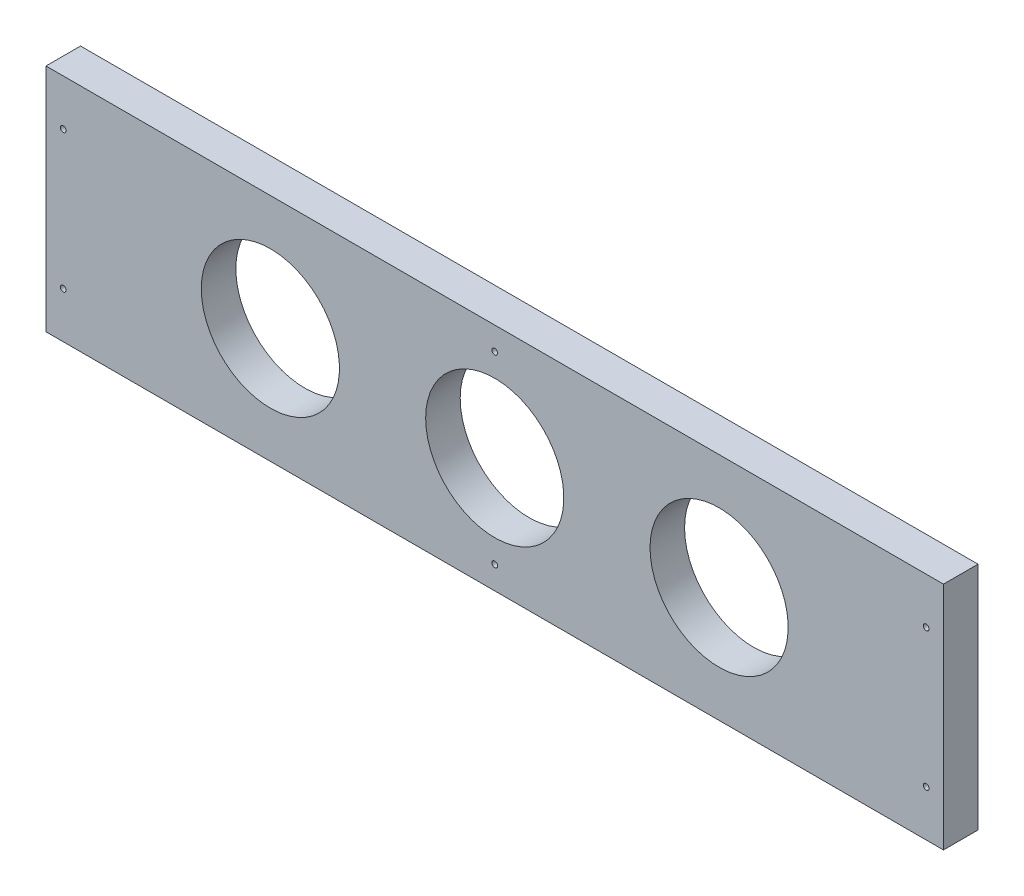
SolidWorks part; units mm, degrees
material "Beech"
ref_plane "Front Plane" through (0, 0, 0) normal (0, 0, 1) x (1, 0, 0)
ref_plane "Top Plane" through (0, 0, 0) normal (0, 1, 0) x (1, 0, 0)
ref_plane "Right Plane" through (0, 0, 0) normal (1, 0, 0) x (0, 0, -1)
sketch "Sketch1" plane through (0, 0, 0) normal (0, 0, 1) x (1, 0, 0)
  line L0 (-157.3266, 4967.6971) -> (-157.3266, 5284.8315) construction
  line L5 (-157.3266, 5411.8315) -> (337.7194, 5411.8315)
  line L6 (-157.3266, 5411.8315) -> (-157.3266, 5284.8315)
  line L7 (-157.3266, 5284.8315) -> (337.7194, 5284.8315)
  line L9 (90.1964, 5267.1362) -> (90.1964, 5460.8032) construction
  line L10 (26.6964, 5267.1362) -> (153.6964, 5267.1362) construction
  line L11 (-176.3766, 5460.8032) -> (356.7694, 5460.8032) construction
  line L12 (-157.3266, 5348.3315) -> (90.1964, 5348.3315) construction
  line L13 (337.7194, 5411.8315) -> (337.7194, 5284.8315)
  point P12 (-76.4911, 5348.3315)
  point P17 (90.1964, 5411.8315)
  point P18 (90.1964, 5284.8315)
  dimension "D1" = 127
extrude "Boss-Extrude1" add sketch "Sketch1" along normal blind 19.05
sketch "Sketch2" plane through (0, 0, 0) normal (0, 0, -1) x (-1, 0, 0)
  line L0 (-337.7194, 5348.3315) -> (-90.1964, 5348.3315) construction
  line L1 (-337.7194, 5284.8315) -> (-337.7194, 5411.8315) construction
  line L3 (-90.1964, 5411.8315) -> (-90.1964, 5284.8315) construction
  line L4 (-337.7194, 5411.8315) -> (157.3266, 5411.8315) construction
  line L5 (157.3266, 5284.8315) -> (-337.7194, 5284.8315) construction
  circle A0 centre (-213.9579, 5348.3315) radius 38.1
  circle A1 centre (-90.1964, 5348.3315) radius 38.1
  circle A2 centre (33.5651, 5348.3315) radius 38.1
  dimension "D1" = 76.2
  dimension "D2" = 123.7615
extrude "Cut-Extrude1" cut sketch "Sketch2" against normal through all
hole_wizard "Hole1" positions "Sketch3" profile "Sketch4" legacy
sketch "Sketch3" plane through (90.1964, 2347.3215, 38.1) normal (0, 0, 1) x (1, 0, 0)
  line L0 (-237.998, 3140.71) -> (-237.998, 2683.51) construction
  line L9 (0, 3140.71) -> (0, 2683.51) construction
  point P13 (-237.998, 3089.91)
  point P15 (-237.998, 3039.11)
  point P17 (-237.998, 2962.91)
  point P19 (-237.998, 2912.11)
  point P21 (-237.998, 2835.91)
  point P23 (-237.998, 2785.11)
  point P25 (-237.998, 2708.91)
  point P38 (237.998, 2708.91)
  point P39 (237.998, 2785.11)
  point P40 (237.998, 2835.91)
  point P41 (237.998, 2912.11)
  point P42 (237.998, 2962.91)
  point P43 (237.998, 3039.11)
  point P44 (237.998, 3089.91)
  point P50 (0, 3051.81)
  point P52 (0, 2950.21)
  point P54 (0, 2797.81)
  point P56 (0, 2696.21)
sketch "Sketch4" plane through (90.1964, 5043.5315, 38.1) normal (1, 0, 0) x (0, -1, 0)
  line L0 (0, 0) -> (0, 51.7539)
  line L1 (0, 51.7539) -> (1.5875, 50.8)
  line L2 (1.5875, 50.8) -> (1.5875, 4.0177)
  line L3 (1.5875, 4.0177) -> (5.08, 0)
  line L4 (5.08, 0) -> (0, 0)
  line L5 (0, -14.3089) -> (0, 102.4216) construction
  line L6 (0, 51.7539) -> (-1.5875, 50.8) construction
  line L7 (-1.5875, 4.0177) -> (-5.08, 0) construction
  dimension "Diameter" = 3.175
  dimension "Depth" = 50.8
  dimension "C-Sink Diameter" = 10.16
  dimension "C-Sink Angle" = 82
  dimension "Drill Angle" = 118
